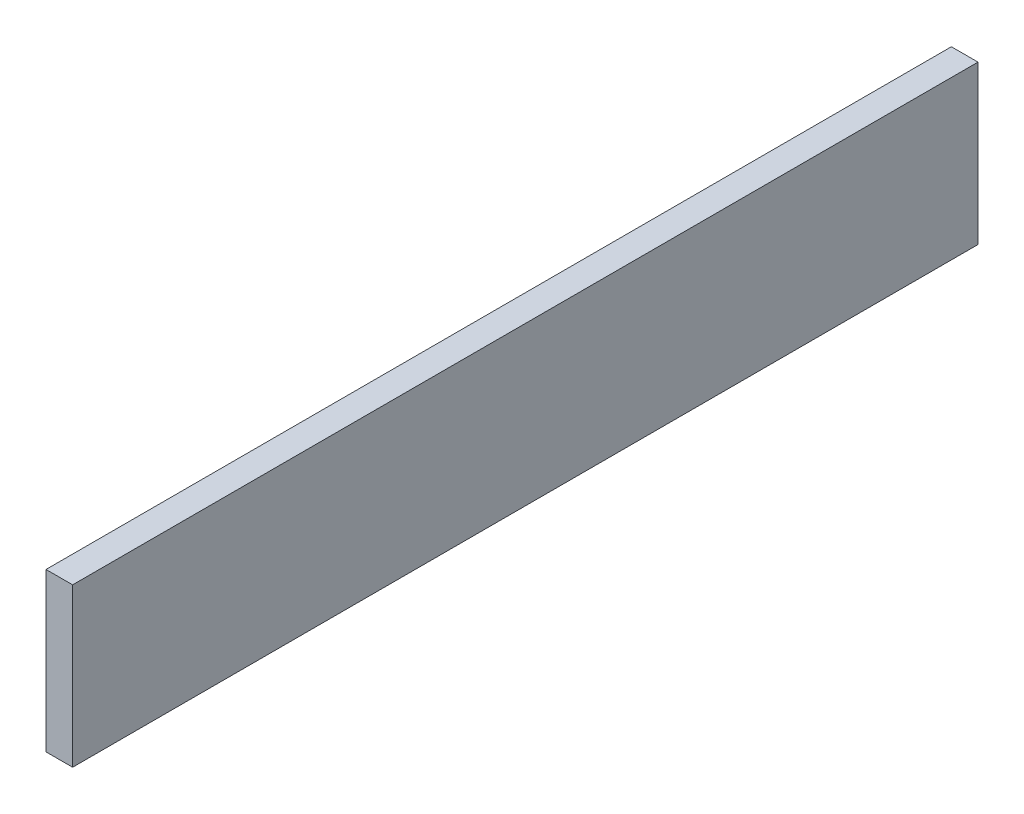
SolidWorks part; units mm, degrees
ref_plane "Alzado" through (0, 0, 0) normal (0, 0, 1) x (1, 0, 0)
ref_plane "Planta" through (0, 0, 0) normal (0, 1, 0) x (1, 0, 0)
ref_plane "Vista lateral" through (0, 0, 0) normal (1, 0, 0) x (0, 0, -1)
sketch "Croquis1" plane through (0, 0, 0) normal (1, 0, 0) x (0, 0, -1)
  line L1 (0, 0) -> (510, 0)
  line L2 (0, 0) -> (0, 89)
  line L3 (0, 89) -> (510, 89)
  line L4 (510, 0) -> (510, 89)
  dimension "D1" = 89
  dimension "D2" = 510
extrude "Saliente-Extruir1" add sketch "Croquis1" along normal blind 15
sketch "Croquis2" plane through (15, 0, 0) normal (1, 0, 0) x (0, 0, -1)
  line L0 (255, 0) -> (255, 89) construction
  line L1 (0, 0) -> (510, 0) construction
  line L2 (510, 89) -> (0, 89) construction
  line L3 (0, 44.5) -> (510, 44.5) construction
  line L4 (0, 89) -> (0, 0) construction
  line L5 (510, 0) -> (510, 89) construction
